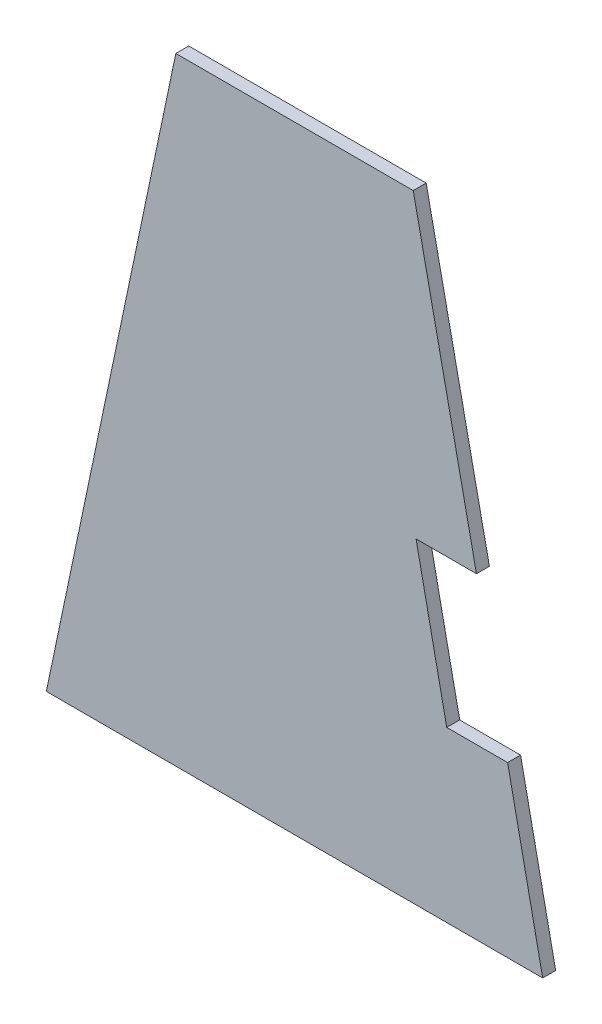
SolidWorks part; units mm, degrees
ref_plane "Front Plane" through (0, 0, 0) normal (0, 0, 1) x (1, 0, 0)
ref_plane "Top Plane" through (0, 0, 0) normal (0, 1, 0) x (1, 0, 0)
ref_plane "Right Plane" through (0, 0, 0) normal (1, 0, 0) x (0, 0, -1)
sketch "Sketch1" plane through (0, 0, 0) normal (0, 0, 1) x (1, 0, 0)
  line L0 (0, 0) -> (115, 0)
  line L1 (115, 0) -> (106.8711, 39.1653)
  line L2 (106.8711, 39.1653) -> (92.7655, 39.1653)
  line L3 (92.7655, 39.1653) -> (85.6527, 73.4349)
  line L4 (85.6527, 73.4349) -> (99.6527, 73.4349)
  line L5 (99.6527, 73.4349) -> (85, 143)
  line L6 (85, 143) -> (30, 143)
  line L7 (30, 143) -> (0, 0)
  line L8 (57.5, 143) -> (57.5, 0) construction
  dimension "D1" = 115
  dimension "D2" = 143
  dimension "D3" = 14
  dimension "D4" = 40
  dimension "D5" = 35
  dimension "D6" = 55
extrude "Boss-Extrude1" add sketch "Sketch1" along normal blind 3 contours L5 L6 L7 L0 L1 L2 L3 L4
